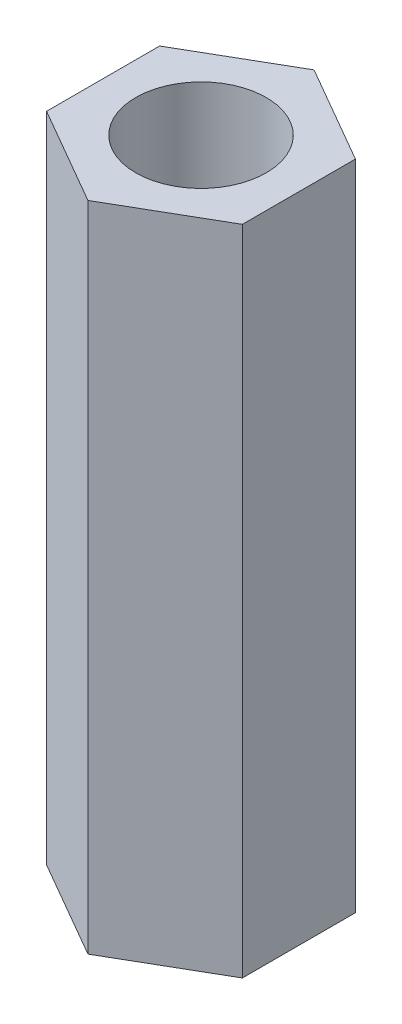
SolidWorks part; units mm, degrees
ref_plane "Alzado" through (0, 0, 0) normal (0, 0, 1) x (1, 0, 0)
ref_plane "Planta" through (0, 0, 0) normal (0, 1, 0) x (1, 0, 0)
ref_plane "Vista lateral" through (0, 0, 0) normal (1, 0, 0) x (0, 0, -1)
sketch "Croquis1" plane through (0, 0, 0) normal (0, 1, 0) x (1, 0, 0)
  line L1 (0, -2.5981) -> (2.25, -1.299)
  line L2 (2.25, -1.299) -> (2.25, 1.299)
  line L3 (2.25, 1.299) -> (0, 2.5981)
  line L4 (0, 2.5981) -> (-2.25, 1.299)
  line L5 (-2.25, 1.299) -> (-2.25, -1.299)
  line L6 (-2.25, -1.299) -> (0, -2.5981)
  circle A0 centre (0, 0) radius 2.25 construction
  circle A1 centre (0, 0) radius 1.5
  dimension "D2" = 3
  dimension "D1" = 4.5
extrude "Saliente-Extruir1" add sketch "Croquis1" along normal blind 15
